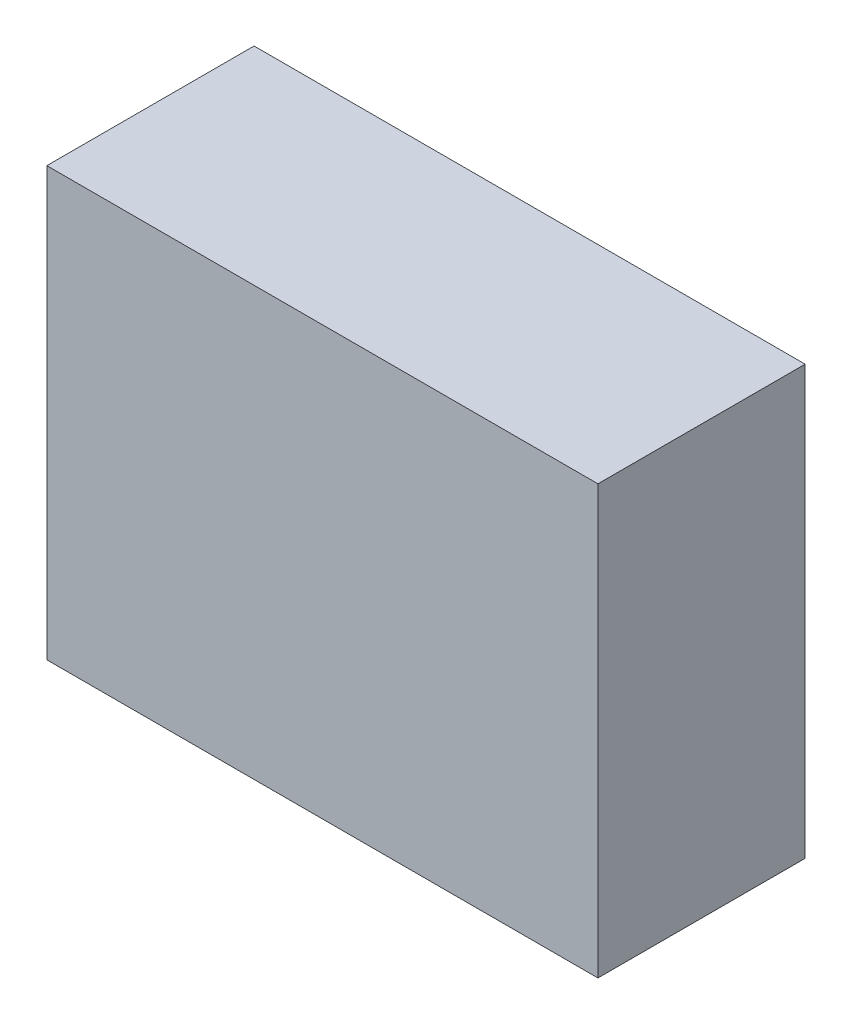
SolidWorks part; units mm, degrees
ref_plane "Front Plane" through (0, 0, 0) normal (0, 0, 1) x (1, 0, 0)
ref_plane "Top Plane" through (0, 0, 0) normal (0, 1, 0) x (1, 0, 0)
ref_plane "Right Plane" through (0, 0, 0) normal (1, 0, 0) x (0, 0, -1)
sketch "Sketch1" plane through (0, 0, 0) normal (0, 0, 1) x (1, 0, 0)
  line L1 (111.2422, -51.3297) -> (71.3527, -51.3297)
  line L2 (111.2422, -51.3297) -> (111.2422, -20.3506)
  line L3 (111.2422, -20.3506) -> (71.3527, -20.3506)
  line L4 (71.3527, -51.3297) -> (71.3527, -20.3506)
extrude "Boss-Extrude1" add sketch "Sketch1" along normal blind 15
